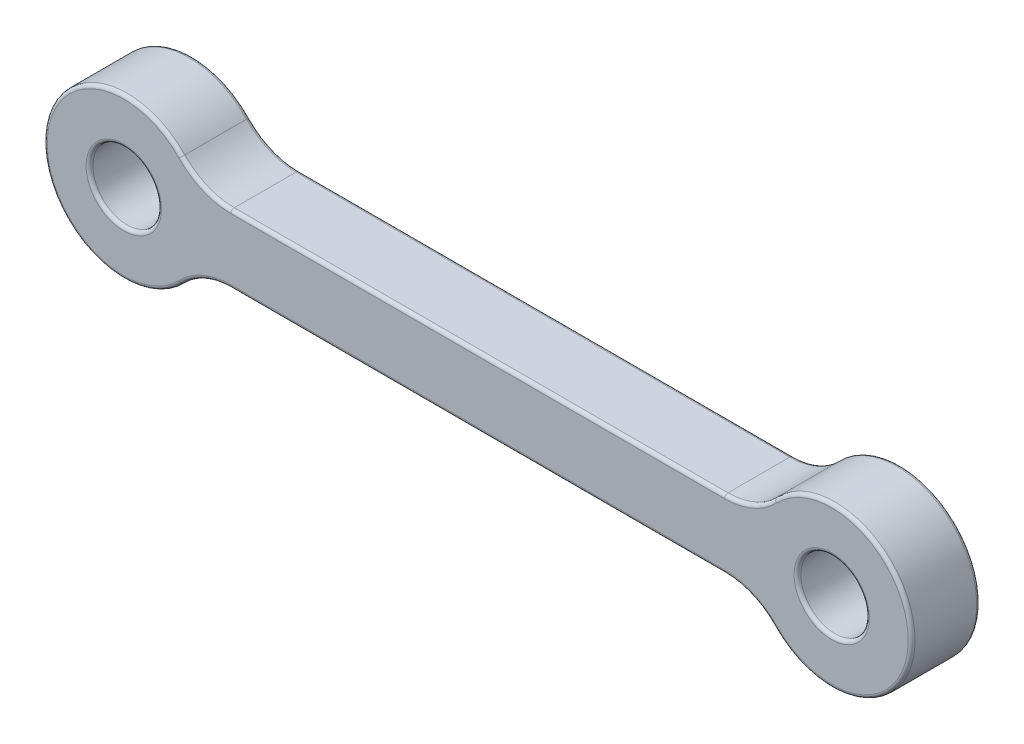
SolidWorks part; units mm, degrees
material "ABS"
ref_plane "Спереди" through (0, 0, 0) normal (0, 0, 1) x (1, 0, 0)
ref_plane "Сверху" through (0, 0, 0) normal (0, 1, 0) x (1, 0, 0)
ref_plane "Справа" through (0, 0, 0) normal (1, 0, 0) x (0, 0, -1)
sketch "Эскиз1" plane through (0, 0, 0) normal (0, 0, 1) x (1, 0, 0)
  line L0 (0, 0) -> (31, 0) construction
  line L1 (0, 3.5) -> (31, 3.5) construction
  line L2 (0, -3.5) -> (31, -3.5) construction
  line L3 (15.5, 0) -> (15.5, -3.5) construction
  line L5 (27.8377, -1.5) -> (3.1623, -1.5)
  line L6 (27.8377, -1.5) -> (27.8377, 1.5) construction
  line L7 (27.8377, 1.5) -> (3.1623, 1.5)
  line L8 (3.1623, -1.5) -> (3.1623, 1.5) construction
  line L9 (27.8377, -1.5) -> (3.1623, 1.5) construction
  line L10 (27.8377, 1.5) -> (3.1623, -1.5) construction
  arc A0 (0, 3.5) -> (0, -3.5) centre (0, 0) ccw construction
  arc A1 (31, -3.5) -> (31, 3.5) centre (31, 0) ccw construction
  circle A2 centre (0, 0) radius 1.5
  circle A3 centre (0, 0) radius 3.5
  circle A4 centre (31, 0) radius 3.5
  circle A5 centre (31, 0) radius 1.5
  point P3 (15.5, 0)
  dimension "D3" = 3
  dimension "D1" = 31
  dimension "D2" = 7
  dimension "D4" = 3
extrude "Бобышка-Вытянуть1" add sketch "Эскиз1" along normal blind 3 contours A3 A2 | L5 A4 L7 A3 | A4 A5
fillet "Скругление1" radius 3 4 edges at (27.8377, 1.5, 1.5) (3.1623, 1.5, 1.5) (27.8377, -1.5, 1.5) (3.1623, -1.5, 1.5)
fillet "Скругление2" radius 0.15 20 edges at (32.5, 0, 0) (3.5137, -1.7404, 0) (15.5, -1.5, 0) (27.4863, -1.7404, 0) (34.5, 0, 0) (27.4863, 1.7404, 0) (15.5, 1.5, 0) (3.5137, 1.7404, 0) (-3.5, 0, 0) (1.5, 0, 0) (32.5, 0, 3) (27.4863, 1.7404, 3) (34.5, 0, 3) (27.4863, -1.7404, 3) (15.5, -1.5, 3) (3.5137, -1.7404, 3) (-3.5, 0, 3) (3.5137, 1.7404, 3) (15.5, 1.5, 3) (1.5, 0, 3)
scale "Масштаб1" scale about centroid uniform scaling yes scale factor 2.2
equation "\"Scale\"= 1"
